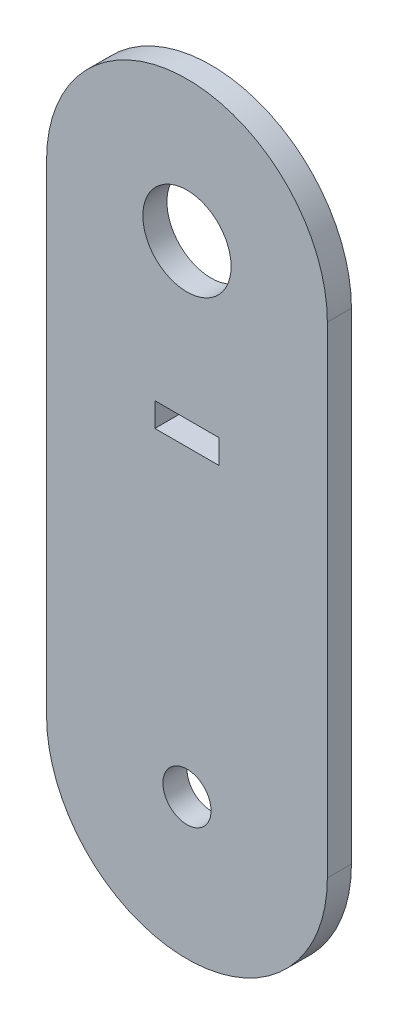
SolidWorks part; units mm, degrees
ref_plane "Alzado" through (0, 0, 0) normal (0, 0, 1) x (1, 0, 0)
ref_plane "Planta" through (0, 0, 0) normal (0, 1, 0) x (1, 0, 0)
ref_plane "Vista lateral" through (0, 0, 0) normal (1, 0, 0) x (0, 0, -1)
sketch "Croquis1" plane through (0, 0, 0) normal (0, 0, 1) x (1, 0, 0)
  line L1 (-17.5, -30) -> (17.5, -30) construction
  line L2 (-17.5, -30) -> (-17.5, 30)
  line L3 (-17.5, 30) -> (17.5, 30) construction
  line L4 (17.5, -30) -> (17.5, 30)
  line L5 (-17.5, -30) -> (17.5, 30) construction
  line L6 (-17.5, 30) -> (17.5, -30) construction
  arc A0 (-17.5, 30) -> (17.5, 30) centre (0, 30) cw
  circle A1 centre (0, 30) radius 5.5
  arc A2 (-17.5, -30) -> (17.5, -30) centre (0, -30) ccw
  circle A3 centre (0, -30) radius 3
  point P0 (0, 0)
  dimension "D3" = 11
  dimension "D4" = 6
  dimension "D1" = 60
  dimension "D2" = 35
extrude "Saliente-Extruir1" add sketch "Croquis1" along normal blind 3
sketch "Croquis2" plane through (0, 0, 3) normal (0, 0, 1) x (1, 0, 0)
  line L0 (-17.5, 10.77) -> (17.5, 10.77) construction
  line L1 (-17.5, 30) -> (-17.5, -30) construction
  line L2 (17.5, -30) -> (17.5, 30) construction
  line L3 (0, -30) -> (0, 47.5) construction
  line L4 (4, 10.77) -> (-4, 10.77)
  line L5 (4, 10.77) -> (4, 7.77)
  line L6 (4, 7.77) -> (-4, 7.77)
  line L7 (-4, 10.77) -> (-4, 7.77)
  arc A0 (17.5, 30) -> (-17.5, 30) centre (0, 30) ccw construction
  point P6 (0, 30)
  point P7 (0, 10.77)
  point P15 (0, 0)
  point P24 (0, -30)
  point P25 (0, -30)
  dimension "D1" = 19.23
  dimension "D2" = 8
  dimension "D3" = 3
extrude "Cortar-Extruir1" cut sketch "Croquis2" against normal up to next
